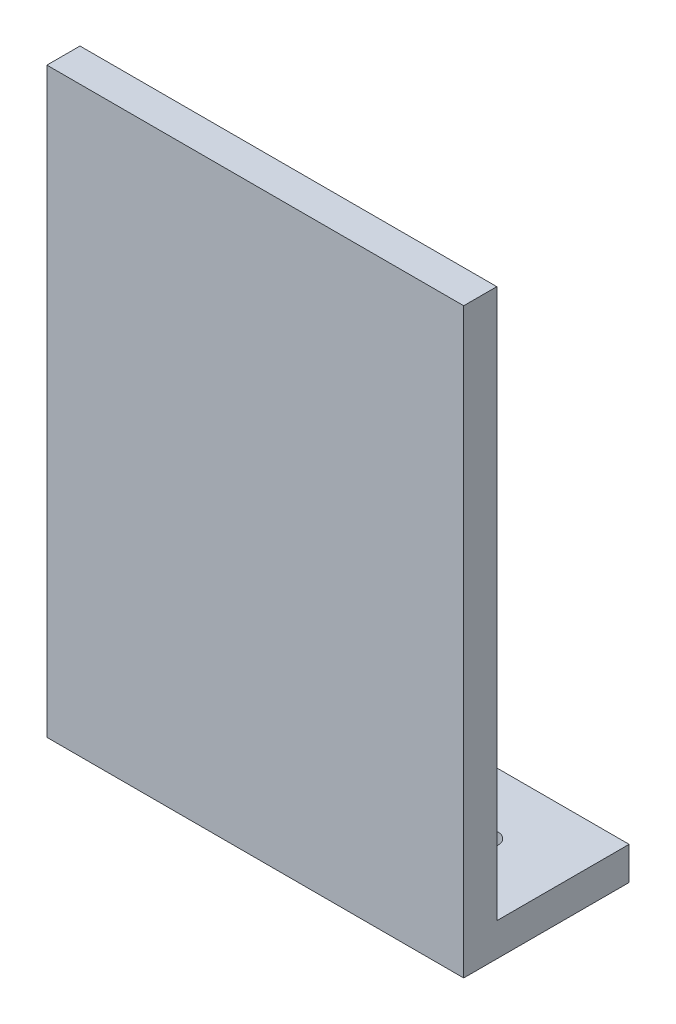
SolidWorks part; units mm, degrees
ref_plane "Front Plane" through (0, 0, 0) normal (0, 0, 1) x (1, 0, 0)
ref_plane "Top Plane" through (0, 0, 0) normal (0, 1, 0) x (1, 0, 0)
ref_plane "Right Plane" through (0, 0, 0) normal (1, 0, 0) x (0, 0, -1)
sketch "Sketch1" plane through (0, 0, 0) normal (0, 0, 1) x (1, 0, 0)
  line L1 (0, 0) -> (63, 0)
  line L2 (0, 0) -> (0, 88)
  line L3 (0, 88) -> (63, 88)
  line L4 (63, 0) -> (63, 88)
  dimension "D1" = 63
  dimension "D2" = 88
extrude "Boss-Extrude1" add sketch "Sketch1" along normal blind 5
sketch "Sketch2" plane through (0, 0, 0) normal (0, 0, -1) x (-1, 0, 0)
  line L0 (-63, 0) -> (-63, 88) construction
  line L1 (0, 0) -> (-63, 0)
  line L2 (0, 0) -> (0, 5)
  line L3 (0, 5) -> (-63, 5)
  line L4 (-63, 0) -> (-63, 5)
  dimension "D1" = 5
extrude "Boss-Extrude2" add sketch "Sketch2" along normal blind 20
sketch "Sketch3" plane through (0, 5, 0) normal (0, 1, 0) x (1, 0, 0)
  line L0 (31.5, 20) -> (31.5, 0) construction
  line L1 (63, 10) -> (0, 10) construction
  line L2 (0, 20) -> (63, 20) construction
  line L3 (63, 0) -> (0, 0) construction
  line L4 (63, 20) -> (63, 0) construction
  line L5 (0, 20) -> (0, 0) construction
  circle A3 centre (51.5, 10) radius 1.7
  circle A4 centre (11.5, 10) radius 1.7
  point P16 (42.5774, 14.0063)
  point P17 (43.178, 10)
  point P18 (19.822, 10)
  point P19 (47.9827, 10)
  point P20 (22.0909, 10)
  point P21 (19.4216, 10)
  dimension "D1" = 3.4
  dimension "D2" = 20
  dimension "D3" = 20
extrude "Cut-Extrude1" cut sketch "Sketch3" against normal through all
